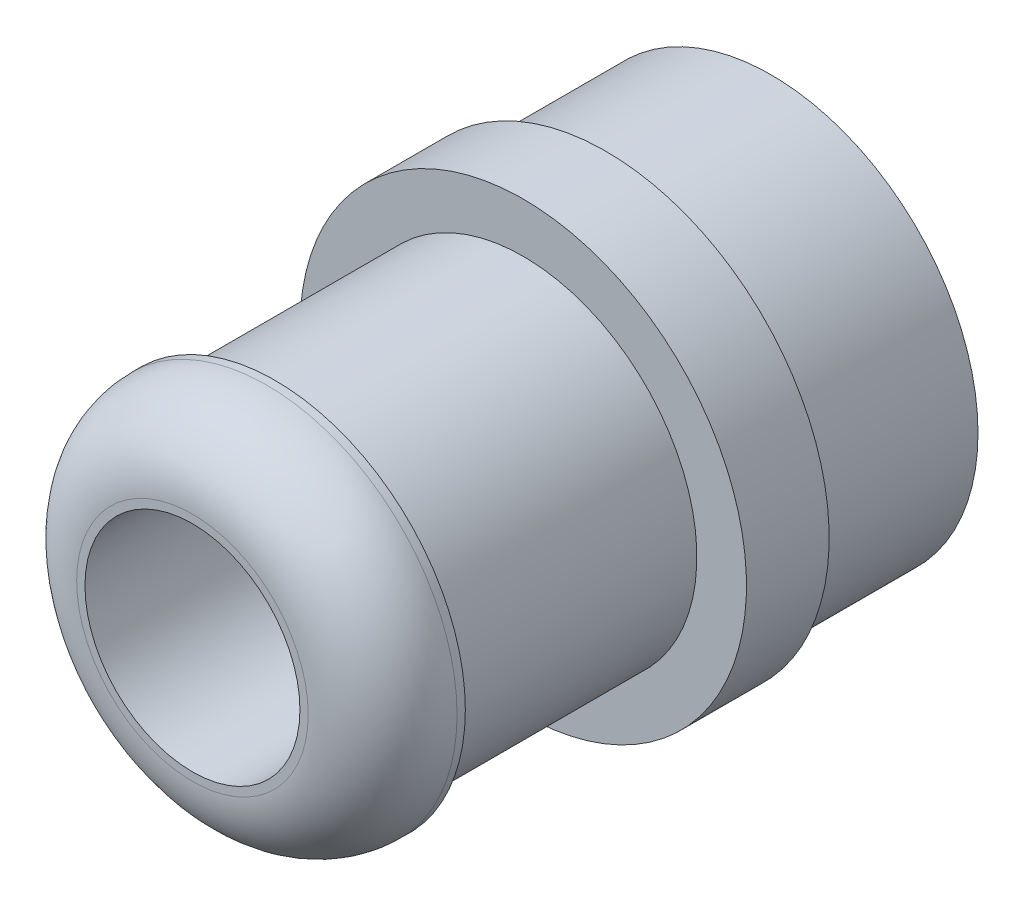
SolidWorks part; units mm, degrees
ref_plane "Front Plane" through (0, 0, 0) normal (0, 0, 1) x (1, 0, 0)
ref_plane "Top Plane" through (0, 0, 0) normal (0, 1, 0) x (1, 0, 0)
ref_plane "Right Plane" through (0, 0, 0) normal (1, 0, 0) x (0, 0, -1)
sketch "Sketch1" plane through (0, 0, 0) normal (0, 0, 1) x (1, 0, 0)
  circle A0 centre (0, 0) radius 2.1
  circle A1 centre (0, 0) radius 1.3
extrude "Boss-Extrude1" add sketch "Sketch1" along normal blind 7
sketch "Sketch2" plane through (0, 0, 0) normal (0, 0, -1) x (-1, 0, 0)
  circle A0 centre (0, 0) radius 2.1
  circle A1 centre (0, 0) radius 2.5
extrude "Boss-Extrude2" add sketch "Sketch2" against normal blind 3
sketch "Sketch3" plane through (0, 0, 7) normal (0, 0, 1) x (1, 0, 0)
  circle A0 centre (0, 0) radius 2.1
  circle A1 centre (0, 0) radius 2.3
extrude "Boss-Extrude3" add sketch "Sketch3" against normal blind 1
sketch "Sketch4" plane through (0, 0, 0) normal (0, 0, -1) x (-1, 0, 0)
  circle A0 centre (0, 0) radius 2.5
  circle A1 centre (0, 0) radius 2.7
extrude "Boss-Extrude4" add sketch "Sketch4" against normal up to surface (1 mm away) from offset 2 up to face at (-2.1, 0, 3) offset against normal yes
fillet "Fillet1" radius 0.9 1 edges at (2.3, 0, 7)
